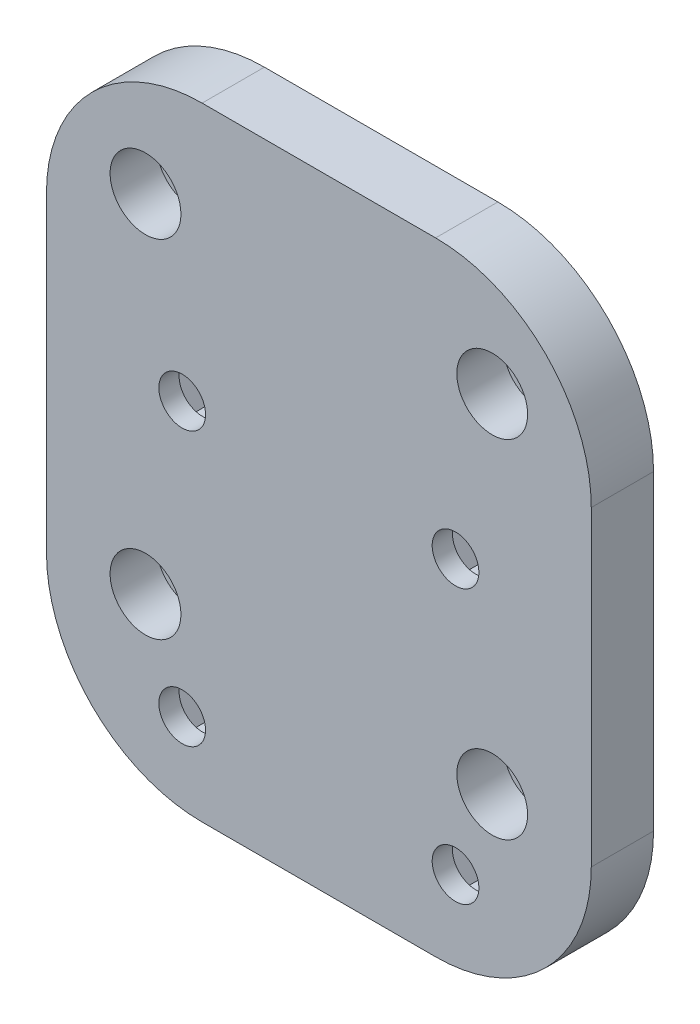
SolidWorks part; units mm, degrees
ref_plane "前视基准面" through (0, 0, 0) normal (0, 0, 1) x (1, 0, 0)
ref_plane "上视基准面" through (0, 0, 0) normal (0, 1, 0) x (1, 0, 0)
ref_plane "右视基准面" through (0, 0, 0) normal (1, 0, 0) x (0, 0, -1)
sketch "草图1" plane through (0, 0, 0) normal (0, 0, 1) x (1, 0, 0)
  line L0 (0, 0) -> (0, 36.8895) construction
  line L2 (-35, 40) -> (35, 40)
  line L3 (-35, 40) -> (-35, -40)
  line L4 (-35, -40) -> (35, -40)
  line L5 (35, 40) -> (35, -40)
  dimension "D1" = 70
  dimension "D2" = 80
  dimension "D3" = 35
  dimension "D4" = 40
extrude "凸台-拉伸1" add sketch "草图1" along normal blind 8 contours L2 L5 L4 L3
sketch "草图7" plane through (0, 0, 8) normal (0, 0, 1) x (1, 0, 0)
  line L0 (0, 0) -> (0, 40) construction
  line L1 (-35, 40) -> (35, 40) construction
  line L3 (-7.5, 40) -> (7.5, 40)
  line L4 (-7.5, 40) -> (-7.5, 18)
  line L5 (-7.5, 18) -> (7.5, 18)
  line L6 (7.5, 40) -> (7.5, 18)
  dimension "D1" = 22
  dimension "D2" = 15
  dimension "D3" = 7.5
sketch "草图2" plane through (0, 0, 8) normal (0, 0, 1) x (1, 0, 0)
  line L0 (0, 0) -> (0, -40) construction
  line L1 (-35, -40) -> (35, -40) construction
  line L2 (-23.6474, -4.5) -> (32.5152, -4.5) construction
  line L3 (-25.0117, -24.5) -> (44.0357, -24.5) construction
  line L4 (-19.0329, -4.5) -> (-17.8955, -4.5)
  line L5 (17.8955, -4.5) -> (19.0329, -4.5)
  line L6 (17.8955, -24.5) -> (19.0329, -24.5)
  line L7 (-19.0329, -24.5) -> (-17.8955, -24.5)
  arc A0 (-17.8955, -4.5) -> (-17.8955, -24.5) centre (0, -14.5) ccw
  arc A1 (-19.0329, -4.5) -> (-19.0329, -24.5) centre (0, -14.5) ccw
  arc A2 (17.8955, -24.5) -> (17.8955, -4.5) centre (0, -14.5) ccw
  arc A3 (19.0329, -24.5) -> (19.0329, -4.5) centre (0, -14.5) ccw
  dimension "D1" = 25.5
  dimension "D2" = 10
  dimension "D4" = 21.5
  dimension "D5" = 20.5
  dimension "D3" = 20
sketch "草图5" plane through (0, 0, 0) normal (0, 0, -1) x (-1, 0, 0)
  line L0 (0, 30) -> (0, -40) construction
  line L2 (35, -40) -> (-35, -40) construction
  point P6 (-13.5, 24.75)
  point P7 (-28, -24.75)
  point P8 (28, -24.75)
  point P9 (13.5, 24.75)
  dimension "D1" = 13.5
  dimension "D2" = 28
  dimension "D3" = 49.5
  dimension "D4" = 24.75
sketch "草图9" plane through (0, 0, 0) normal (0, 0, 1) x (1, 0, 0)
  line L0 (35, 17.5) -> (29, 17.5)
  line L1 (35, 40) -> (35, -40) construction
  line L2 (29, 17.5) -> (29, -17.5)
  line L3 (35, 17.5) -> (35, -17.5)
  line L4 (0, 0) -> (46.0009, 0) construction
  line L5 (35, -17.5) -> (29, -17.5)
  line L6 (0, 0) -> (0, 43.2165) construction
  line L7 (-35, -17.5) -> (-29, -17.5)
  line L8 (-29, 17.5) -> (-29, -17.5)
  line L9 (-35, 17.5) -> (-29, 17.5)
  line L10 (-35, 17.5) -> (-35, -17.5)
  point P12 (29, 0)
  dimension "D1" = 35
  dimension "D2" = 6
sketch "草图11" plane through (0, 0, 0) normal (0, 0, 1) x (1, 0, 0)
  line L0 (0, 36.6897) -> (0, -57.9108) construction
  line L1 (0, 30) -> (0, -40) construction
  line L2 (0, 4) -> (-52.3712, 4) construction
  line L3 (0, 4) -> (-36.4685, 40.4685) construction
  circle A0 centre (0, 4) radius 31.5 construction
  circle A1 centre (-22.2739, 26.2739) radius 3
  circle A2 centre (22.2739, 26.2739) radius 3
  circle A3 centre (22.2739, -18.2739) radius 3
  circle A4 centre (-22.2739, -18.2739) radius 3
  point P20 (0, 4)
  dimension "D1" = 63
  dimension "D4" = 6
  dimension "D2" = 4
  dimension "D3" = 45
  dimension "D5" = 4
extrude "切除-拉伸4" cut sketch "草图11" along normal blind 15
sketch "草图13" plane through (0, 0, 8) normal (0, 0, 1) x (1, 0, 0)
  line L0 (0, 30) -> (0, -52.7857) construction
  circle A0 centre (-22.2739, 26.2739) radius 4.55
  circle A1 centre (-22.2739, -18.2739) radius 4.55
  circle A2 centre (22.2739, -18.2739) radius 4.55
  circle A3 centre (22.2739, 26.2739) radius 4.55
  dimension "D1" = 9.1
  dimension "D2" = 9.1
extrude "切除-拉伸6" cut sketch "草图13" against normal blind 6
sketch "草图14" plane through (0, 0, 8) normal (0, 0, 1) x (1, 0, 0)
  line L0 (-17.56, 5.56) -> (0, -12) construction
  line L1 (0, -12) -> (-30.4629, -12) construction
  line L2 (0, 0) -> (29.6874, 0) construction
  circle A0 centre (-17.56, 5.56) radius 3
  circle A1 centre (17.56, 5.56) radius 3
  circle A2 centre (17.56, -29.56) radius 3
  circle A3 centre (-17.56, -29.56) radius 3
  point P2 (0, -12)
  point P16 (0, -12)
  dimension "D5" = 6
  dimension "D1" = 45
  dimension "D2" = 17.56
  dimension "D3" = 12
  dimension "D4" = 4
extrude "切除-拉伸7" cut sketch "草图14" against normal blind 16
sketch "草图15" plane through (0, 0, 0) normal (0, 0, -1) x (-1, 0, 0)
  line L0 (0, 0) -> (0, -22.5326) construction
  line L1 (-14.7137, 0.63) -> (-11.8673, 5.56)
  line L2 (-11.8673, 5.56) -> (-14.7137, 10.49)
  line L3 (-14.7137, 10.49) -> (-20.4063, 10.49)
  line L4 (-20.4063, 10.49) -> (-23.2527, 5.56)
  line L5 (-23.2527, 5.56) -> (-20.4063, 0.63)
  line L6 (-20.4063, 0.63) -> (-14.7137, 0.63)
  line L7 (-14.7137, -34.49) -> (-11.8673, -29.56)
  line L8 (-11.8673, -29.56) -> (-14.7137, -24.63)
  line L9 (-14.7137, -24.63) -> (-20.4063, -24.63)
  line L10 (-20.4063, -24.63) -> (-23.2527, -29.56)
  line L11 (-23.2527, -29.56) -> (-20.4063, -34.49)
  line L12 (-20.4063, -34.49) -> (-14.7137, -34.49)
  line L13 (20.4063, -34.49) -> (14.7137, -34.49)
  line L14 (23.2527, -29.56) -> (20.4063, -34.49)
  line L15 (20.4063, -24.63) -> (23.2527, -29.56)
  line L16 (14.7137, -24.63) -> (20.4063, -24.63)
  line L17 (11.8673, -29.56) -> (14.7137, -24.63)
  line L18 (14.7137, -34.49) -> (11.8673, -29.56)
  line L19 (20.4063, 0.63) -> (14.7137, 0.63)
  line L20 (23.2527, 5.56) -> (20.4063, 0.63)
  line L21 (20.4063, 10.49) -> (23.2527, 5.56)
  line L22 (14.7137, 10.49) -> (20.4063, 10.49)
  line L23 (11.8673, 5.56) -> (14.7137, 10.49)
  line L24 (14.7137, 0.63) -> (11.8673, 5.56)
  circle A0 centre (17.56, -29.56) radius 3 construction
  circle A1 centre (-17.56, -29.56) radius 3 construction
  circle A2 centre (17.56, 5.56) radius 3 construction
  circle A3 centre (-17.56, 5.56) radius 3 construction
  circle A4 centre (17.56, -29.56) radius 3 construction
  circle A5 centre (-17.56, -29.56) radius 3 construction
  circle A6 centre (17.56, 5.56) radius 3 construction
  circle A7 centre (-17.56, 5.56) radius 3 construction
  circle A8 centre (-17.56, 5.56) radius 4.93 construction
  circle A9 centre (-17.56, -29.56) radius 4.93 construction
  circle A10 centre (17.56, -29.56) radius 4.93 construction
  circle A11 centre (17.56, 5.56) radius 4.93 construction
  circle A12 centre (17.56, 5.56) radius 3 construction
  circle A13 centre (17.56, -29.56) radius 3 construction
  point P12 (-13.2905, 3.095)
  point P27 (-13.2905, -32.025)
  point P28 (-21.8295, -27.095)
  dimension "D1" = 9.86
  dimension "D2" = 9.86
extrude "切除-拉伸8" cut sketch "草图15" against normal blind 5.4
fillet "圆角1" radius 20 4 edges at (-35, -40, 4) (35, -40, 4) (35, 40, 4) (-35, 40, 4)
